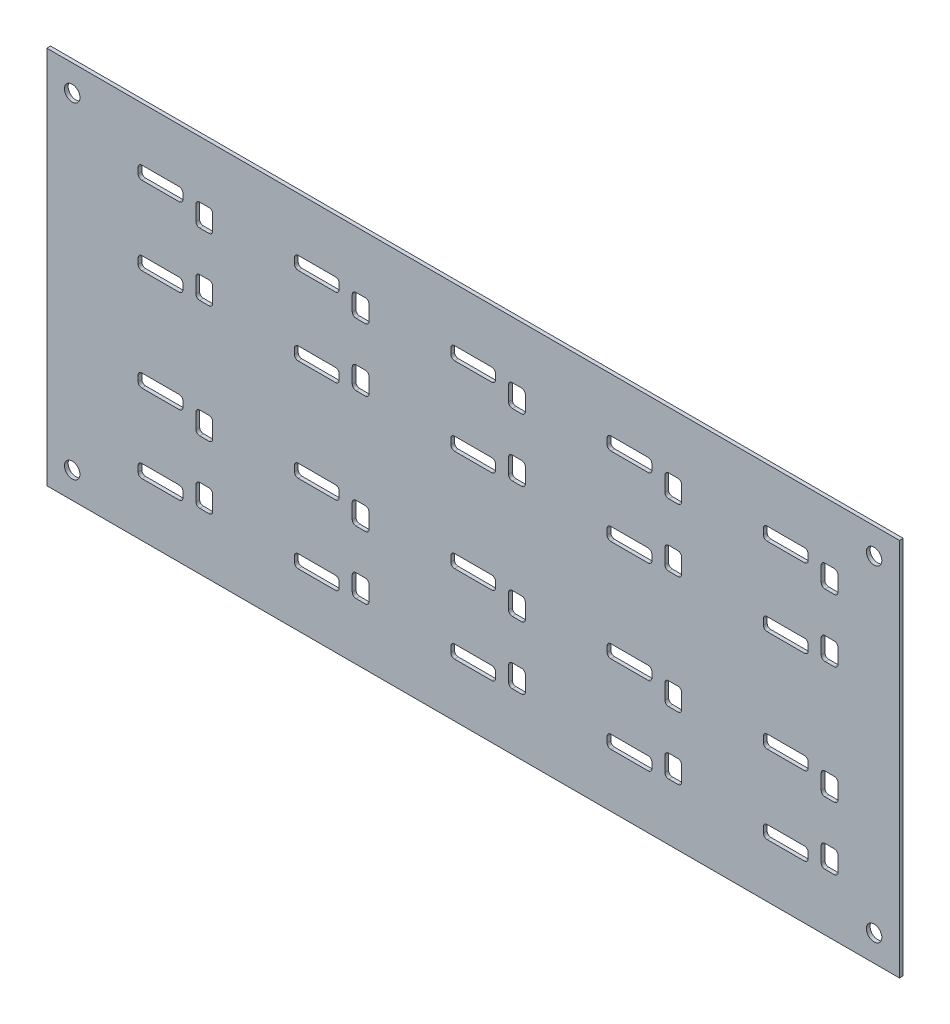
SolidWorks part; units mm, degrees
ref_plane "Front Plane" through (0, 0, 0) normal (0, 0, 1) x (1, 0, 0)
ref_plane "Top Plane" through (0, 0, 0) normal (0, 1, 0) x (1, 0, 0)
ref_plane "Right Plane" through (0, 0, 0) normal (1, 0, 0) x (0, 0, -1)
sketch "Sketch1" plane through (0, 0, 0) normal (0, 0, 1) x (1, 0, 0)
  line L1 (228.6, 101.6) -> (-228.6, 101.6)
  line L2 (228.6, 101.6) -> (228.6, -101.6)
  line L3 (228.6, -101.6) -> (-228.6, -101.6)
  line L4 (-228.6, 101.6) -> (-228.6, -101.6)
  line L5 (228.6, 101.6) -> (-228.6, -101.6) construction
  line L6 (228.6, -101.6) -> (-228.6, 101.6) construction
  point P0 (0, 0)
  dimension "D1" = 203.2
  dimension "D2" = 457.2
extrude "Boss-Extrude1" add sketch "Sketch1" along normal blind 2
sketch "Sketch2" plane through (0, 0, 0) normal (0, 0, -1) x (-1, 0, 0)
  line L0 (167.6273, -65.7734) -> (167.6273, -72.7734) construction
  line L1 (179.6273, -69.2734) -> (155.6273, -69.2734) construction
  line L5 (155.6273, -72.7734) -> (179.6273, -72.7734)
  line L6 (155.6273, -72.7734) -> (155.6273, -65.7734)
  line L7 (155.6273, -65.7734) -> (179.6273, -65.7734)
  line L8 (179.6273, -72.7734) -> (179.6273, -65.7734)
  line L9 (155.6273, -72.7734) -> (179.6273, -65.7734) construction
  line L10 (155.6273, -65.7734) -> (179.6273, -72.7734) construction
  line L13 (0, 101.6) -> (0, -101.6) construction
  line L14 (-228.6, 101.6) -> (228.6, 101.6) construction
  line L15 (228.6, -101.6) -> (-228.6, -101.6) construction
  line L16 (228.6, 0) -> (-228.6, 0) construction
  line L17 (228.6, 101.6) -> (228.6, -101.6) construction
  line L18 (-228.6, -101.6) -> (-228.6, 101.6) construction
  point P6 (167.6273, -69.2734)
  point P11 (167.6273, -69.2734)
  dimension "D1" = 7
  dimension "D2" = 24
  dimension "D3" = 167.6273
  dimension "D4" = 69.2734
extrude "Cut-Extrude1" cut sketch "Sketch2" against normal through all
pattern_linear "LPattern1" count 2 spacing 42.0281 along (0, 1, 0) of "Cut-Extrude1"
pattern_linear "LPattern2" count 5 spacing 83.82 along (1, 0, 0) count 2 spacing 96.52 along (0, 1, 0) of "LPattern1", "Cut-Extrude1"
fillet "Fillet1" radius 2 80 edges at (-95.8073, 30.7466, 1) (-95.8073, 23.7466, 1) (-71.8073, 23.7466, 1) (-71.8073, 30.7466, 1) (-95.8073, 72.7747, 1) (-95.8073, 65.7747, 1) (-71.8073, 65.7747, 1) (-71.8073, 72.7747, 1) (-11.9873, -65.7734, 1) (-11.9873, -72.7734, 1) (12.0127, -72.7734, 1) (12.0127, -65.7734, 1) (-11.9873, -23.7453, 1) (-11.9873, -30.7453, 1) (12.0127, -30.7453, 1) (12.0127, -23.7453, 1) (-11.9873, 30.7466, 1) (-11.9873, 23.7466, 1) (12.0127, 23.7466, 1) (12.0127, 30.7466, 1) (-11.9873, 72.7747, 1) (-11.9873, 65.7747, 1) (12.0127, 65.7747, 1) (12.0127, 72.7747, 1) (71.8327, -65.7734, 1) (71.8327, -72.7734, 1) (95.8327, -72.7734, 1) (95.8327, -65.7734, 1) (-179.6273, -65.7734, 1) (71.8327, -23.7453, 1) (71.8327, -30.7453, 1) (95.8327, -30.7453, 1) (95.8327, -23.7453, 1) (-179.6273, -72.7734, 1) (-155.6273, -72.7734, 1) (-155.6273, -65.7734, 1) (71.8327, 30.7466, 1) (71.8327, 23.7466, 1) (95.8327, 23.7466, 1) (95.8327, 30.7466, 1) (71.8327, 72.7747, 1) (71.8327, 65.7747, 1) (95.8327, 65.7747, 1) (95.8327, 72.7747, 1) (155.6527, -65.7734, 1) (155.6527, -72.7734, 1) (179.6527, -72.7734, 1) (179.6527, -65.7734, 1) (155.6527, -23.7453, 1) (155.6527, -30.7453, 1) (179.6527, -30.7453, 1) (179.6527, -23.7453, 1) (155.6527, 30.7466, 1) (155.6527, 23.7466, 1) (179.6527, 23.7466, 1) (179.6527, 30.7466, 1) (155.6527, 72.7747, 1) (155.6527, 65.7747, 1) (179.6527, 65.7747, 1) (179.6527, 72.7747, 1) (-179.6273, -23.7453, 1) (-179.6273, -30.7453, 1) (-155.6273, -30.7453, 1) (-155.6273, -23.7453, 1) (-179.6273, 30.7466, 1) (-179.6273, 23.7466, 1) (-155.6273, 23.7466, 1) (-155.6273, 30.7466, 1) (-179.6273, 72.7747, 1) (-179.6273, 65.7747, 1) (-155.6273, 65.7747, 1) (-155.6273, 72.7747, 1) (-95.8073, -65.7734, 1) (-95.8073, -72.7734, 1) (-71.8073, -72.7734, 1) (-71.8073, -65.7734, 1) (-95.8073, -23.7453, 1) (-95.8073, -30.7453, 1) (-71.8073, -30.7453, 1) (-71.8073, -23.7453, 1)
hole_wizard "Ø8.3 (8.3) Diameter Hole1" positions "Sketch4" profile "Sketch3" hole size "Ø8.3" standard "ANSI Metric" end condition through all
sketch "Sketch4" plane through (0, 0, 0) normal (0, 0, -1) x (-1, 0, 0)
  point P0 (-215, 87.5)
  point P3 (-215, -87.5)
  point P6 (215, -87.5)
  point P9 (215, 87.5)
  dimension "D1" = 430
  dimension "D2" = 175
  dimension "D3" = 87.5
  dimension "D4" = 215
sketch "Sketch3" plane through (215, 87.5, 0) normal (1, 0, 0) x (0, 1, 0)
  line L0 (0, 0) -> (0, 2)
  line L1 (0, 2) -> (4.15, 2)
  line L2 (4.15, 2) -> (4.15, 0)
  line L5 (4.15, 0) -> (0, 0)
  line L11 (0, -6.35) -> (0, 107.95) construction
  dimension "Thru Hole Dia." = 8.3
  dimension "Thru Hole Depth" = 2
sketch "Sketch5" plane through (0, 0, 0) normal (0, 0, -1) x (-1, 0, 0)
  line L0 (-228.6, 65.0748) -> (228.6, 65.0748) construction
  line L1 (-186.635, 71.0748) -> (-195.635, 71.0748)
  line L2 (-186.635, 71.0748) -> (-186.635, 59.0748)
  line L3 (-186.635, 59.0748) -> (-195.635, 59.0748)
  line L4 (-195.635, 71.0748) -> (-195.635, 59.0748)
  line L5 (-186.635, 71.0748) -> (-195.635, 59.0748) construction
  line L6 (-186.635, 59.0748) -> (-195.635, 71.0748) construction
  line L7 (-186.635, 37.4452) -> (-195.635, 37.4452)
  line L8 (-186.635, 37.4452) -> (-186.635, 25.4452)
  line L9 (-186.635, 25.4452) -> (-195.635, 25.4452)
  line L10 (-195.635, 37.4452) -> (-195.635, 25.4452)
  line L11 (-186.635, 37.4452) -> (-195.635, 25.4452) construction
  line L12 (-186.635, 25.4452) -> (-195.635, 37.4452) construction
  line L13 (-228.6, -101.6) -> (-228.6, 101.6) construction
  line L14 (228.6, 101.6) -> (228.6, -101.6) construction
  line L15 (-228.6, 31.4452) -> (228.6, 31.4452) construction
  line L16 (-228.6, 101.6) -> (228.6, 101.6) construction
  line L17 (-191.135, 101.6) -> (-191.135, -101.6) construction
  line L18 (228.6, -101.6) -> (-228.6, -101.6) construction
  point P0 (-191.135, 65.0748)
  point P7 (-191.135, 31.4452)
  dimension "D1" = 37.465
  dimension "D2" = 36.5252
  dimension "D3" = 70.1548
  dimension "D4" = 9
  dimension "D5" = 12
  dimension "D6" = 12
  dimension "D7" = 9
extrude "Cut-Extrude2" cut sketch "Sketch5" against normal through all
fillet "Fillet2" radius 2 8 edges at (186.635, 59.0748, 1) (195.635, 59.0748, 1) (195.635, 71.0748, 1) (186.635, 37.4452, 1) (186.635, 25.4452, 1) (195.635, 25.4452, 1) (195.635, 37.4452, 1) (186.635, 71.0748, 1)
pattern_linear "LPattern3" count 5 spacing 83.82 along (-1, 0, 0) count 2 spacing 96.52 along (0, -1, 0) of "Cut-Extrude2", "Fillet2"
